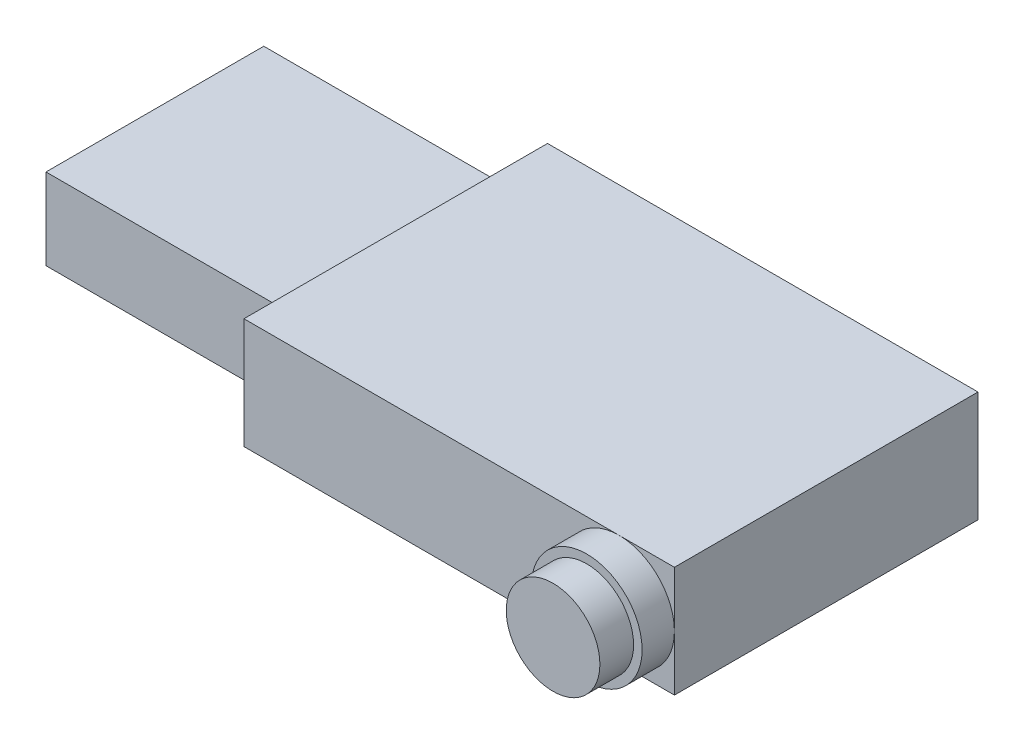
SolidWorks part; units mm, degrees
ref_plane "Front Plane" through (0, 0, 0) normal (0, 0, 1) x (1, 0, 0)
ref_plane "Top Plane" through (0, 0, 0) normal (0, 1, 0) x (1, 0, 0)
ref_plane "Right Plane" through (0, 0, 0) normal (1, 0, 0) x (0, 0, -1)
sketch "Sketch1" plane through (0, 0, 0) normal (0, 1, 0) x (1, 0, 0)
  line L1 (0, 0) -> (23.6982, 0)
  line L2 (0, 0) -> (0, 16.7132)
  line L3 (0, 16.7132) -> (23.6982, 16.7132)
  line L4 (23.6982, 0) -> (23.6982, 16.7132)
  dimension "D1" = 23.6982
  dimension "D2" = 16.7132
extrude "Boss-Extrude1" add sketch "Sketch1" along normal blind 6.096
sketch "Sketch2" plane through (0, 0, 0) normal (-1, 0, 0) x (0, 0, 1)
  line L0 (-10.2376, 6.096) -> (-10.2376, 5.2832) construction
  line L1 (-14.351, 5.2832) -> (-2.3622, 5.2832)
  line L2 (-14.351, 5.2832) -> (-14.351, 0.8128)
  line L3 (-14.351, 0.8128) -> (-2.3622, 0.8128)
  line L4 (-2.3622, 5.2832) -> (-2.3622, 0.8128)
  line L5 (-16.7132, 6.096) -> (0, 6.096) construction
  line L6 (-10.2376, 0.8128) -> (-10.2376, 0) construction
  line L7 (-16.7132, 0) -> (0, 0) construction
  line L8 (-16.7132, 4.0613) -> (-14.351, 4.0613) construction
  line L9 (-16.7132, 6.096) -> (-16.7132, 0) construction
  line L10 (-2.3622, 4.0613) -> (0, 4.0613) construction
  line L11 (0, 6.096) -> (0, 0) construction
  dimension "D1" = 11.9888
  dimension "D2" = 4.4704
extrude "Boss-Extrude2" add sketch "Sketch2" along normal blind 13.2588
sketch "Sketch3" plane through (-13.2588, 0, 0) normal (-1, 0, 0) x (0, 0, 1)
  line L1 (-14.0462, 3.175) -> (-2.667, 3.175)
  line L2 (-14.0462, 3.175) -> (-14.0462, 1.1176)
  line L3 (-14.0462, 1.1176) -> (-2.667, 1.1176)
  line L4 (-2.667, 3.175) -> (-2.667, 1.1176)
  line L6 (-10.3342, 1.1176) -> (-10.3342, 0.8128) construction
  line L7 (-14.351, 0.8128) -> (-2.3622, 0.8128) construction
  line L8 (-14.351, 2.5059) -> (-14.0462, 2.5059) construction
  line L9 (-14.351, 5.2832) -> (-14.351, 0.8128) construction
  line L10 (-2.667, 2.5059) -> (-2.3622, 2.5059) construction
  line L11 (-2.3622, 0.8128) -> (-2.3622, 5.2832) construction
  dimension "D1" = 0.3048
  dimension "D2" = 2.0574
extrude "Cut-Extrude1" cut sketch "Sketch3" against normal blind 9.017
sketch "Sketch4" plane through (0, 0, 0) normal (0, 0, 1) x (1, 0, 0)
  line L0 (23.6982, 3.048) -> (23.6982, 6.6081) construction
  line L1 (23.6982, 6.096) -> (23.6982, 0) construction
  line L2 (0, 3.048) -> (30.4093, 3.048) construction
  line L3 (0, 6.096) -> (0, 0) construction
  line L4 (0, 6.096) -> (23.6982, 6.096) construction
  circle A0 centre (20.6502, 3.048) radius 3.048
extrude "Boss-Extrude3" add sketch "Sketch4" along normal blind 1.778
sketch "Sketch5" plane through (0, 0, 1.778) normal (0, 0, 1) x (1, 0, 0)
  circle A0 centre (20.6502, 3.048) radius 2.5781
  circle A1 centre (20.6502, 3.048) radius 3.048 construction
  dimension "D1" = 5.1562
extrude "Boss-Extrude4" add sketch "Sketch5" along normal blind 1.8542
